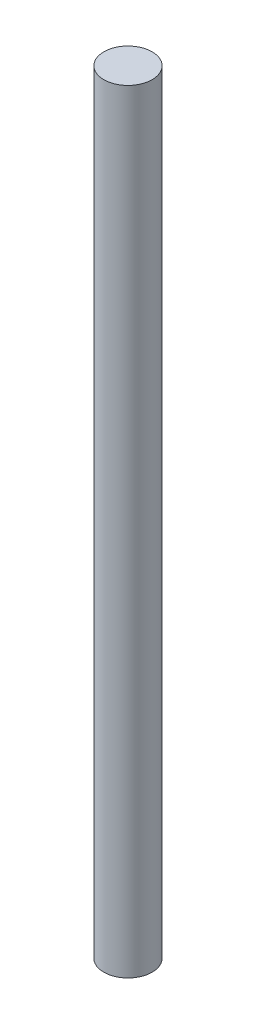
SolidWorks part; units mm, degrees
material "不锈钢 (铁素体)"
ref_plane "前视基准面" through (0, 0, 0) normal (0, 0, 1) x (1, 0, 0)
ref_plane "上视基准面" through (0, 0, 0) normal (0, 1, 0) x (1, 0, 0)
ref_plane "右视基准面" through (0, 0, 0) normal (1, 0, 0) x (0, 0, -1)
other "Configuration Table"
sketch "草图1" plane through (0, 0, 0) normal (0, 1, 0) x (1, 0, 0)
  circle A0 centre (0, 0) radius 2.5
  dimension "D1" = 5
extrude "凸台-拉伸1" add sketch "草图1" along normal blind 80
equation "\"r\"= 5"
equation "\"h\" = 80"
equation "\"D1@草图1\"=\"r\""
equation "\"D1@凸台-拉伸1\"=\"h\""
